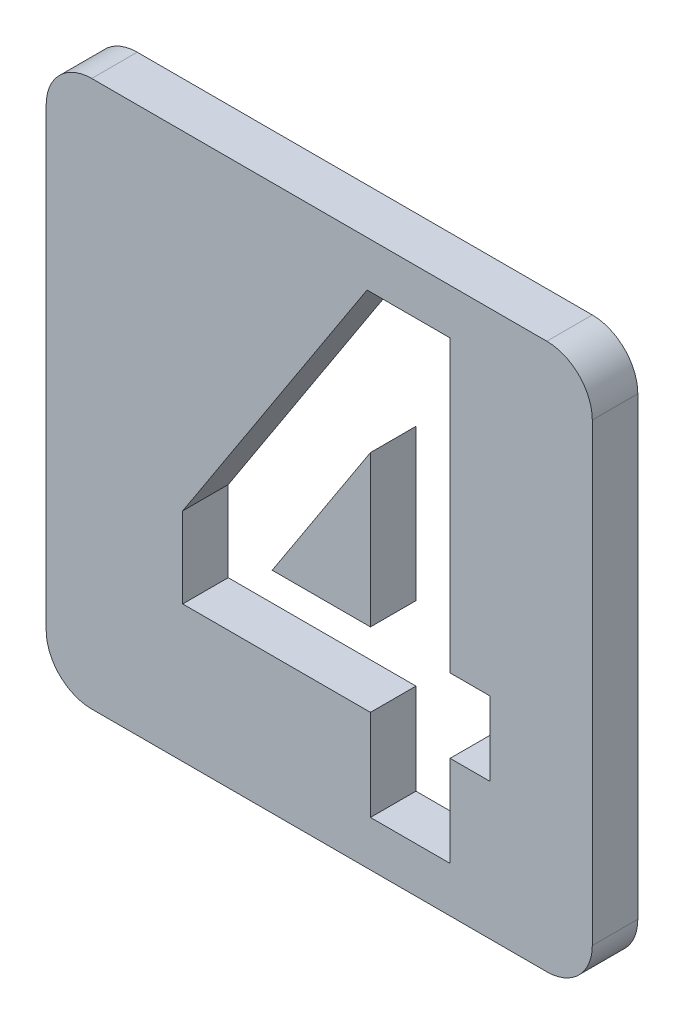
SolidWorks part; units mm, degrees
ref_plane "Front Plane" through (0, 0, 0) normal (0, 0, 1) x (1, 0, 0)
ref_plane "Top Plane" through (0, 0, 0) normal (0, 1, 0) x (1, 0, 0)
ref_plane "Right Plane" through (0, 0, 0) normal (1, 0, 0) x (0, 0, -1)
sketch "Sketch1" plane through (0, 0, 0) normal (0, 0, 1) x (1, 0, 0)
  line L1 (-50, 60) -> (50, 60)
  line L2 (-60, 50) -> (-60, -50)
  line L3 (-50, -60) -> (50, -60)
  line L4 (60, 50) -> (60, -50)
  line L5 (-60, 60) -> (60, -60) construction
  line L6 (-60, -60) -> (60, 60) construction
  arc A0 (-60, -50) -> (-50, -60) centre (-50, -50) ccw
  arc A1 (50, -60) -> (60, -50) centre (50, -50) ccw
  arc A2 (50, 60) -> (60, 50) centre (50, 50) cw
  arc A3 (-50, 60) -> (-60, 50) centre (-50, 50) ccw
  point P0 (0, 0)
  dimension "D3" = 10
  dimension "D1" = 120
  dimension "D2" = 120
extrude "Boss-Extrude1" add sketch "Sketch1" along normal blind 10 contours A3 L2 A0 L3 A1 L4 A2 L1
sketch "Sketch2" plane through (0, 0, 10) normal (0, 0, 1) x (1, 0, 0)
  line L0 (0, 0) -> (0, 40) construction
  line L1 (-50, 50) -> (50, 50) construction
  line L2 (-50, 50) -> (-50, -50) construction
  line L3 (-50, -50) -> (50, -50) construction
  line L4 (50, 50) -> (50, -50) construction
  line L5 (-50, 50) -> (50, -50) construction
  line L6 (-50, -50) -> (50, 50) construction
  line L7 (0, 40) -> (-40, 40) construction
  line L8 (-40, 40) -> (-40, 0) construction
  line L9 (-40, 0) -> (0, 0) construction
  line L11 (0, 20) -> (-20, 20) construction
  line L12 (-20, 40) -> (-20, 20) construction
  circle A0 centre (0, 40) radius 4 construction
  circle A1 centre (0, 20) radius 4 construction
  circle A2 centre (0, 0) radius 4 construction
  circle A3 centre (-20, 20) radius 4 construction
  circle A4 centre (-20, 40) radius 4 construction
  circle A5 centre (-40, 40) radius 4 construction
  circle A6 centre (0, 0) radius 4 construction
  circle A7 centre (20, 0) radius 4 construction
  circle A8 centre (40, 0) radius 4 construction
  circle A9 centre (40, 20) radius 4 construction
  circle A10 centre (40, 40) radius 4 construction
  circle A11 centre (20, 20) radius 4 construction
  circle A12 centre (0, 0) radius 4 construction
  circle A13 centre (0, -20) radius 4 construction
  circle A14 centre (0, -40) radius 4 construction
  circle A15 centre (20, -40) radius 4 construction
  circle A16 centre (40, -40) radius 4 construction
  circle A17 centre (20, -20) radius 4 construction
  circle A18 centre (0, 0) radius 4 construction
  circle A19 centre (-20, 0) radius 4 construction
  circle A20 centre (-40, 0) radius 4 construction
  circle A21 centre (-40, -20) radius 4 construction
  circle A22 centre (-40, -40) radius 4 construction
  circle A23 centre (-20, -20) radius 4 construction
  text T0 "4" font "Century Gothic" height 97.5
  point P0 (0, 0)
  point P55 (0, 0)
  dimension "D4" = 8
  dimension "D1" = 100
  dimension "D2" = 100
  dimension "D3" = 40
  dimension "D5" = 4
extrude "Cut-Extrude2" cut sketch "Sketch2" against normal blind 10
